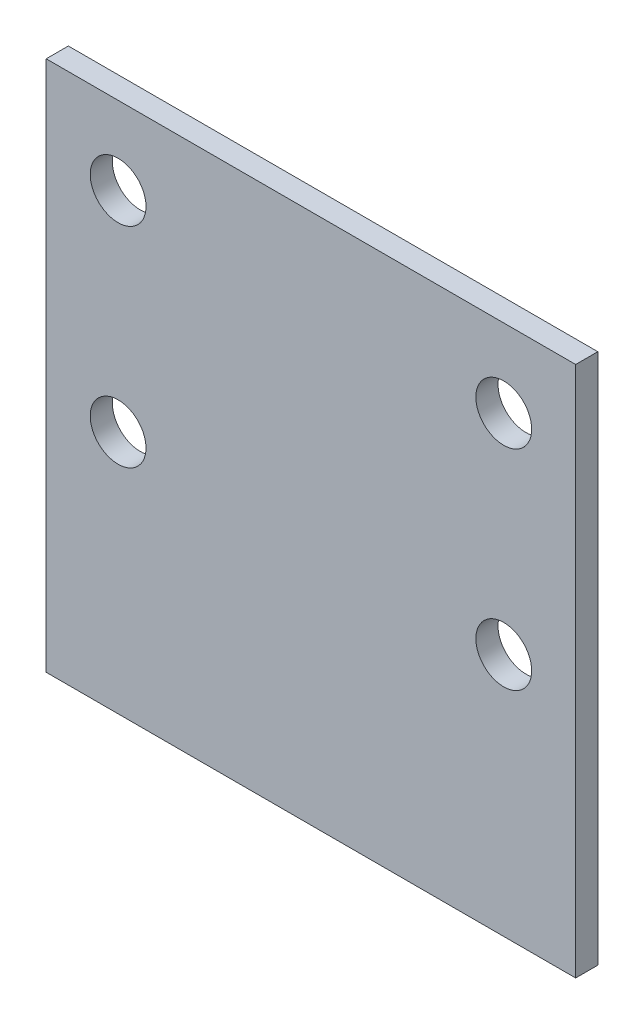
SolidWorks part; units mm, degrees
material "6061-T6 (SS)"
ref_plane "Front Plane" through (0, 0, 0) normal (0, 0, 1) x (1, 0, 0)
ref_plane "Top Plane" through (0, 0, 0) normal (0, 1, 0) x (1, 0, 0)
ref_plane "Right Plane" through (0, 0, 0) normal (1, 0, 0) x (0, 0, -1)
sketch "Sketch1" plane through (0, 0, 0) normal (0, 0, 1) x (1, 0, 0)
  line L0 (-25.4, 0) -> (0, 0) construction
  line L14 (0, 76.2) -> (-25.4, 76.2) construction
  line L15 (-25.4, 76.2) -> (-25.4, 0) construction
  line L17 (50.53, 0) -> (50.53, 76.2) construction
  line L20 (-25.4, 0) -> (50.53, 0)
  line L22 (50.53, 76.2) -> (-25.4, 76.2)
  line L23 (-25.4, 76.2) -> (-25.4, 0)
  line L25 (50.53, 0) -> (50.53, 76.2)
  circle A2 centre (-15.0876, 65) radius 4 construction
  circle A3 centre (-15.0876, 35) radius 4 construction
  circle A4 centre (-15.0876, 65) radius 4
  circle A5 centre (-15.0876, 35) radius 4
  circle A6 centre (40.2176, 65) radius 4 construction
  circle A7 centre (40.2176, 35) radius 4 construction
  circle A8 centre (40.2176, 65) radius 4
  circle A9 centre (40.2176, 35) radius 4
extrude "Boss-Extrude1" add sketch "Sketch1" along normal blind 3.175
